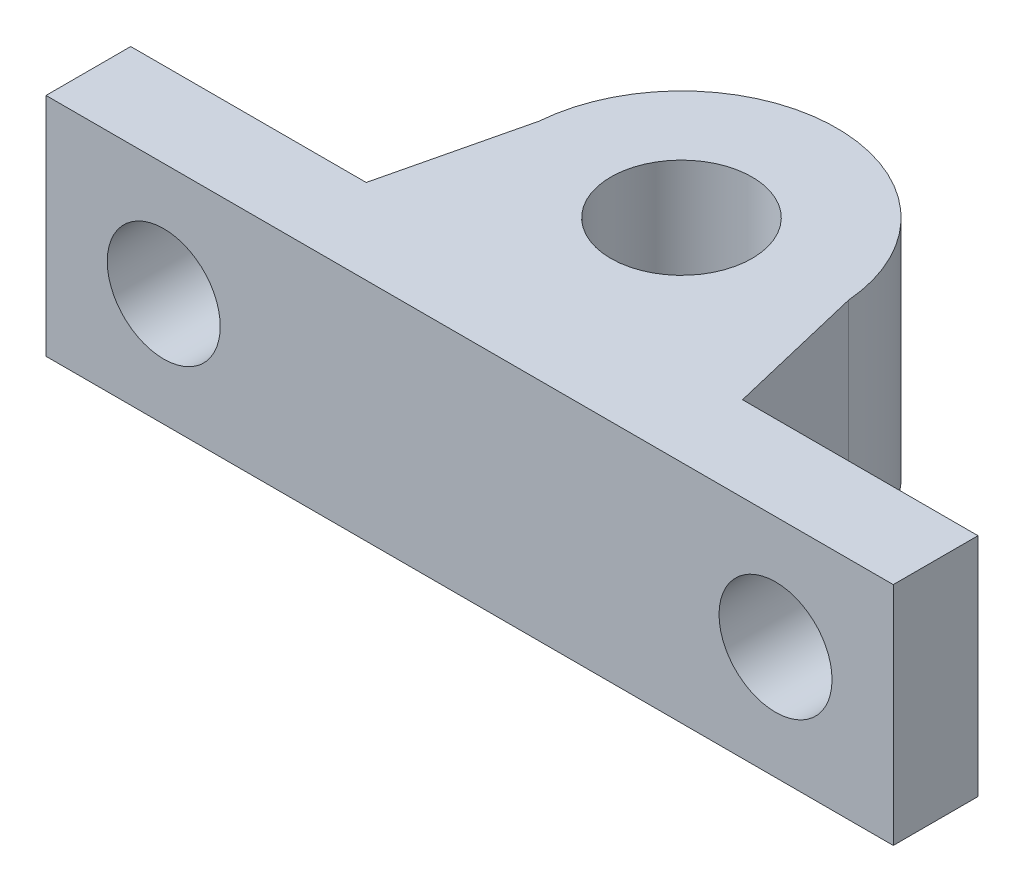
SolidWorks part; units mm, degrees
ref_plane "Front Plane" through (0, 0, 0) normal (0, 0, 1) x (1, 0, 0)
ref_plane "Top Plane" through (0, 0, 0) normal (0, 1, 0) x (1, 0, 0)
ref_plane "Right Plane" through (0, 0, 0) normal (1, 0, 0) x (0, 0, -1)
sketch "Sketch1" plane through (0, 0, 0) normal (0, 1, 0) x (1, 0, 0)
  circle A0 centre (0, 0) radius 2.5
  circle A1 centre (0, 0) radius 5.5
  dimension "D1" = 3
extrude "Boss-Extrude1" add sketch "Sketch1" along normal blind 8
sketch "Sketch2" plane through (0, 8, 0) normal (0, 1, 0) x (1, 0, 0)
  line L0 (0, -2.5) -> (0, -4.5)
  line L1 (5.4823, 0.4408) -> (6.6623, -4.5)
  line L2 (-15, -4.5) -> (15, -4.5)
  line L3 (0, -4.5) -> (0, -7.5)
  line L4 (-15, -7.5) -> (15, -7.5)
  line L5 (15, -4.5) -> (15, -7.5)
  line L6 (-15, -4.5) -> (-15, -7.5)
  line L7 (-5.4823, 0.4408) -> (-6.6623, -4.5)
  circle A0 centre (0, 0) radius 2.5 construction
  circle A1 centre (0, 0) radius 5.5 construction
  circle A2 centre (0, 0) radius 5.5
  circle M4 centre (0, 0) radius 5.5
  dimension "D1" = 2
extrude "Boss-Extrude2" add sketch "Sketch2" against normal blind 8 contours L5 L2 L3 L4 M4 | L2 L1 M4 | L7 L2 M4 | L2 L6 L4 L3 M4
sketch "Sketch3" plane through (0, 0, 4.5) normal (0, 0, -1) x (-1, 0, 0)
  line L0 (-15, 4) -> (-6.6623, 4)
  line L1 (-15, 0) -> (-15, 8) construction
  line L2 (-6.6623, 0) -> (-6.6623, 8) construction
  line L3 (0, 8) -> (0, 10.48)
  line L4 (5.4823, 8) -> (-5.4823, 8) construction
  circle A0 centre (-10.8311, 4) radius 2
  circle A1 centre (10.8311, 4) radius 2
extrude "Cut-Extrude1" cut sketch "Sketch3" against normal blind 8 contours L0 A0 | L0 A0 | A1
